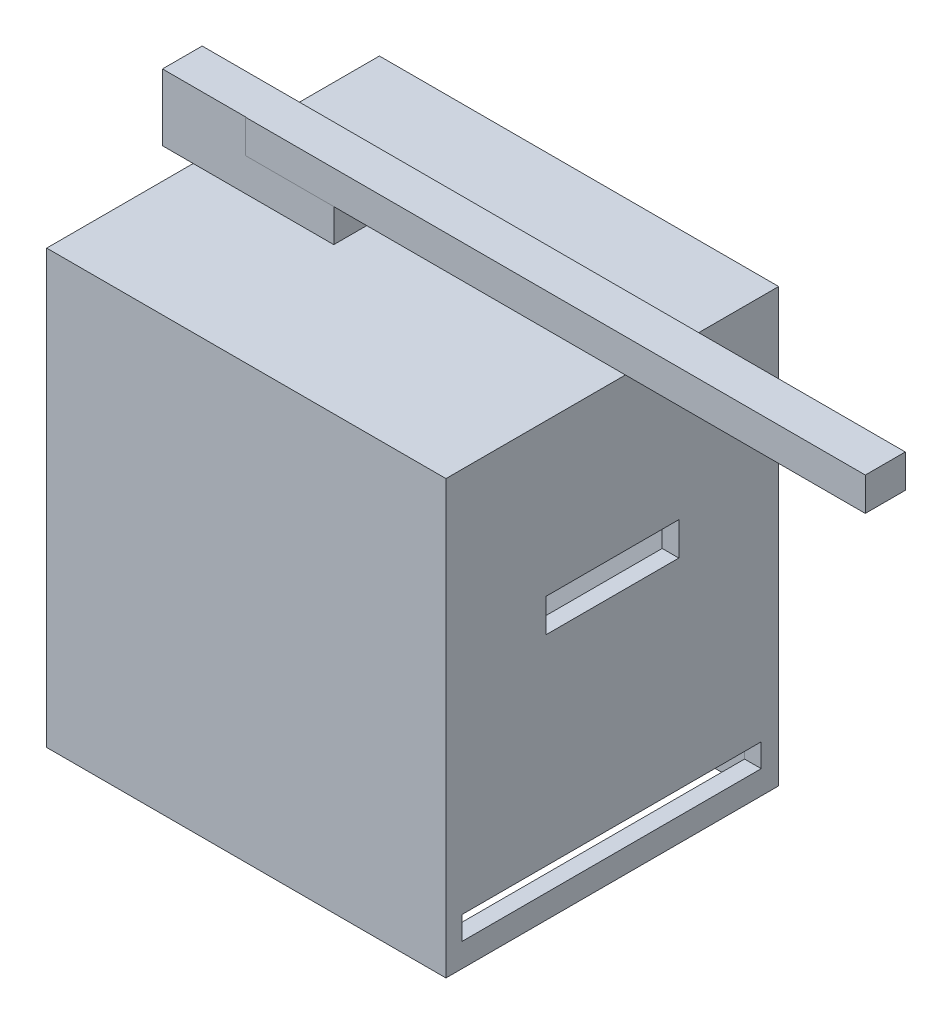
SolidWorks part; units mm, degrees
ref_plane "Front Plane" through (0, 0, 0) normal (0, 0, 1) x (1, 0, 0)
ref_plane "Top Plane" through (0, 0, 0) normal (0, 1, 0) x (1, 0, 0)
ref_plane "Right Plane" through (0, 0, 0) normal (1, 0, 0) x (0, 0, -1)
sketch "Sketch1" plane through (0, 0, 0) normal (0, 1, 0) x (1, 0, 0)
  line L1 (-27.5, 22.5) -> (27.5, 22.5)
  line L2 (-27.5, 22.5) -> (-27.5, -22.5)
  line L3 (-27.5, -22.5) -> (27.5, -22.5)
  line L4 (27.5, 22.5) -> (27.5, -22.5)
  line L5 (-27.5, 22.5) -> (27.5, -22.5) construction
  line L6 (-27.5, -22.5) -> (27.5, 22.5) construction
  line L7 (-30, 25) -> (30, 25)
  line L8 (-30, 25) -> (-30, -25)
  line L9 (-30, -25) -> (30, -25)
  line L10 (30, 25) -> (30, -25)
  line L11 (-30, 25) -> (30, -25) construction
  line L12 (-30, -25) -> (30, 25) construction
  point P0 (0, 0)
  point P6 (0, 0)
  dimension "D1" = 45
  dimension "D2" = 55
  dimension "D3" = 50
  dimension "D4" = 60
extrude "Boss-Extrude1" add sketch "Sketch1" along normal blind 50
sketch "Sketch2" plane through (0, 50, 0) normal (0, 1, 0) x (1, 0, 0)
  line L1 (-30, 25) -> (30, 25)
  line L2 (-30, 25) -> (-30, -25)
  line L3 (-30, -25) -> (30, -25)
  line L4 (30, 25) -> (30, -25)
  line L5 (-30, 25) -> (30, -25) construction
  line L6 (-30, -25) -> (30, 25) construction
  point P0 (0, 0)
  dimension "D1" = 50
  dimension "D2" = 60
extrude "Boss-Extrude2" add sketch "Sketch2" along normal blind 5
sketch "Sketch3" plane through (30, 0, 0) normal (1, 0, 0) x (0, 0, -1)
  line L0 (0, 29.6562) -> (0, 65.0118) construction
  line L1 (0, 29.6562) -> (-30.2573, 29.6562) construction
  line L3 (-10, 32.1562) -> (10, 32.1562)
  line L4 (-10, 32.1562) -> (-10, 27.1562)
  line L5 (-10, 27.1562) -> (10, 27.1562)
  line L6 (10, 32.1562) -> (10, 27.1562)
  line L7 (-10, 32.1562) -> (10, 27.1562) construction
  line L8 (-10, 27.1562) -> (10, 32.1562) construction
  dimension "D1" = 20
  dimension "D2" = 5
extrude "Cut-Extrude1" cut sketch "Sketch3" against normal up to next
sketch "Sketch4" plane through (0, 55, 0) normal (0, 1, 0) x (1, 0, 0)
  line L6 (-34.6178, -2.9834) -> (-8.8748, -2.9834)
  line L7 (-34.6178, -2.9834) -> (-34.6178, 2.9834)
  line L8 (-34.6178, 2.9834) -> (-8.8748, 2.9834)
  line L9 (-8.8748, -2.9834) -> (-8.8748, 2.9834)
  line L10 (-34.6178, -2.9834) -> (-8.8748, 2.9834) construction
  line L11 (-34.6178, 2.9834) -> (-8.8748, -2.9834) construction
  point P0 (-21.7463, 0)
extrude "Boss-Extrude5" add sketch "Sketch4" along normal blind 10
sketch "Sketch8" plane through (0, 65, 0) normal (0, 1, 0) x (1, 0, 0)
  line L0 (-8.8748, 2.9834) -> (-34.6178, 2.9834) construction
  line L1 (-22.0682, 2.9834) -> (71.0495, 2.9834)
  line L2 (-22.0682, 2.9834) -> (-22.0682, -3.0265)
  line L3 (-22.0682, -3.0265) -> (71.0495, -3.0265)
  line L4 (71.0495, 2.9834) -> (71.0495, -3.0265)
extrude "Boss-Extrude6" add sketch "Sketch8" against normal blind 5
sketch "Sketch10" plane through (0, 0, 0) normal (0, -1, 0) x (1, 0, 0)
  line L0 (27.5, -22.5) -> (-27.5, -22.5) construction
  line L1 (-30, 25) -> (30, 25)
  line L2 (-30, 25) -> (-30, -25)
  line L3 (-30, -25) -> (30, -25)
  line L4 (30, 25) -> (30, -25)
  line L5 (-30, 25) -> (30, -25) construction
  line L6 (-30, -25) -> (30, 25) construction
  line L7 (-27.5, 22.5) -> (27.5, 22.5)
  line L8 (-27.5, 22.5) -> (-27.5, -22.5)
  line L9 (-27.5, -22.5) -> (27.5, -22.5)
  line L10 (27.5, 22.5) -> (27.5, -22.5)
  line L11 (-27.5, 22.5) -> (27.5, -22.5) construction
  line L12 (-27.5, -22.5) -> (27.5, 22.5) construction
  line L13 (27.5, -22.5) -> (-27.5, -22.5) construction
  point P0 (0, 0)
  point P7 (0, 0)
extrude "Boss-Extrude7" add sketch "Sketch10" along normal blind 10
sketch "Sketch11" plane through (-30, 0, 0) normal (-1, 0, 0) x (0, 0, 1)
  line L1 (-22.3804, -2.9454) -> (22.6196, -2.9454)
  line L2 (-22.3804, -2.9454) -> (-22.3804, -6.4454)
  line L3 (-22.3804, -6.4454) -> (22.6196, -6.4454)
  line L4 (22.6196, -2.9454) -> (22.6196, -6.4454)
  line L5 (-22.3804, -2.9454) -> (22.6196, -6.4454) construction
  line L6 (-22.3804, -6.4454) -> (22.6196, -2.9454) construction
  point P0 (0.1196, -4.6954)
  dimension "D1" = 3.5
  dimension "D2" = 45
extrude "Cut-Extrude2" cut sketch "Sketch11" against normal through all both and the other way through all
